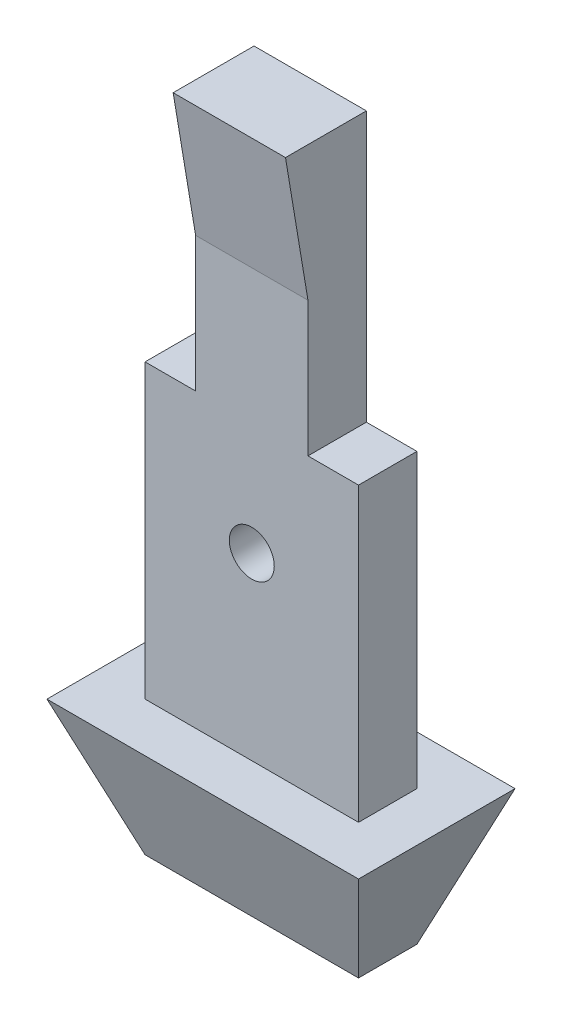
SolidWorks part; units mm, degrees
material "ABS"
ref_plane "Plano frontal" through (0, 0, 0) normal (0, 0, 1) x (1, 0, 0)
ref_plane "Plano superior" through (0, 0, 0) normal (0, 1, 0) x (1, 0, 0)
ref_plane "Plano direito" through (0, 0, 0) normal (1, 0, 0) x (0, 0, -1)
sketch "Esboço1" plane through (0, 0, 0) normal (0, 0, 1) x (1, 0, 0)
  line L0 (0, 0) -> (0, 61.3289) construction
  line L1 (-2.5, 31) -> (2.5, 31)
  line L2 (2.5, 31) -> (2.5, 19)
  line L3 (2.5, 19) -> (4.75, 19)
  line L4 (4.75, 19) -> (4.75, 0)
  line L5 (4.75, 0) -> (-4.75, 0)
  line L6 (-4.75, 19) -> (-4.75, 0)
  line L7 (-2.5, 19) -> (-4.75, 19)
  line L8 (-2.5, 31) -> (-2.5, 19)
  circle A0 centre (0, 14) radius 1
  point P13 (0, 31)
  dimension "D5" = 2
  dimension "D1" = 19
  dimension "D2" = 9.5
  dimension "D3" = 5
  dimension "D4" = 12
  dimension "D6" = 5
extrude "Ressalto-extrusão1" add sketch "Esboço1" along normal blind 2.6
sketch "Esboço2" plane through (0, 0, 0) normal (0, -1, 0) x (1, 0, 0)
  line L4 (-4.75, 0) -> (4.75, 0)
  line L5 (4.75, 0) -> (4.75, 2.6)
  line L6 (4.75, 2.6) -> (-4.75, 2.6)
  line L7 (-4.75, 2.6) -> (-4.75, 0)
  line L8 (-4.75, 0) -> (4.75, 0)
  line L9 (4.75, 0) -> (4.75, 2.6)
  line L10 (4.75, 2.6) -> (-4.75, 2.6)
  line L11 (-4.75, 2.6) -> (-4.75, 0)
  dimension "D1" = 0
extrude "Ressalto-extrusão2" add sketch "Esboço2" against normal blind 6 draft 20
sketch "Esboço3" plane through (2.5, 0, 0) normal (1, 0, 0) x (0, 0, -1)
  line L0 (-2.6, 31) -> (-3.6, 31)
  line L1 (-3.6, 31) -> (-2.6, 25)
  line L2 (-2.6, 19) -> (-2.6, 31) construction
  line L3 (-2.6, 31) -> (-2.6, 25)
  dimension "D1" = 1
extrude "Ressalto-extrusão3" add sketch "Esboço3" against normal up to surface (5 mm away) up to face at (-2.5, 25, 1.3)
